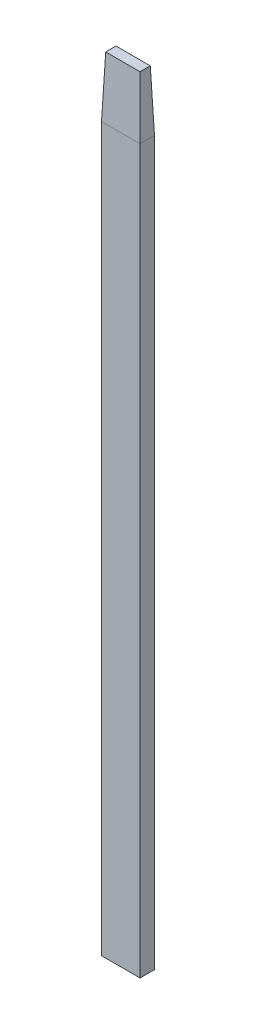
SolidWorks part; units mm, degrees
ref_plane "Plan de face" through (0, 0, 0) normal (0, 0, 1) x (1, 0, 0)
ref_plane "Plan de dessus" through (0, 0, 0) normal (0, 1, 0) x (1, 0, 0)
ref_plane "Plan de droite" through (0, 0, 0) normal (1, 0, 0) x (0, 0, -1)
sketch "Esquisse1" plane through (0, 0, 0) normal (0, 0, 1) x (1, 0, 0)
  line L1 (-4.8, -90) -> (4.8, -90)
  line L2 (-4.8, -90) -> (-4.8, 90)
  line L3 (-4.8, 90) -> (4.8, 90)
  line L4 (4.8, -90) -> (4.8, 90)
  line L5 (-4.8, -90) -> (4.8, 90) construction
  line L6 (-4.8, 90) -> (4.8, -90) construction
  point P0 (0, 0)
  dimension "D1" = 9.6
  dimension "D2" = 180
extrude "Boss.-Extru.1" add sketch "Esquisse1" along normal mid plane 3.6
sketch "Esquisse4" plane through (0, 90, 0) normal (0, 1, 0) x (1, 0, 0)
  line L0 (4.8, 1.8) -> (-4.8, 1.8) construction
  line L1 (-4.8, 1.8) -> (4.8, 1.8)
  line L2 (-4.8, 1.8) -> (-4.8, -1.8)
  line L3 (-4.8, -1.8) -> (4.8, -1.8)
  line L4 (4.8, 1.8) -> (4.8, -1.8)
  line L6 (4.8, -1.8) -> (4.8, 1.8) construction
  line L7 (-4.8, -1.8) -> (-4.8, 1.8) construction
  point P11 (4.8, 0)
extrude "Boss.-Extru.4" add sketch "Esquisse4" along normal blind 15 separate body
draft "Dépouille5" type of draft neutral plane draft angle 2 faces to draft 4 face at (4.8, 97.5, 0) face at (0, 97.5, 1.8) face at (-4.8, 97.5, 0) face at (0, 97.5, -1.8) neutral plane through (0, 90, 0) neutral plane normal (0, -1, 0) reverse direction yes parameters "D1"=2
